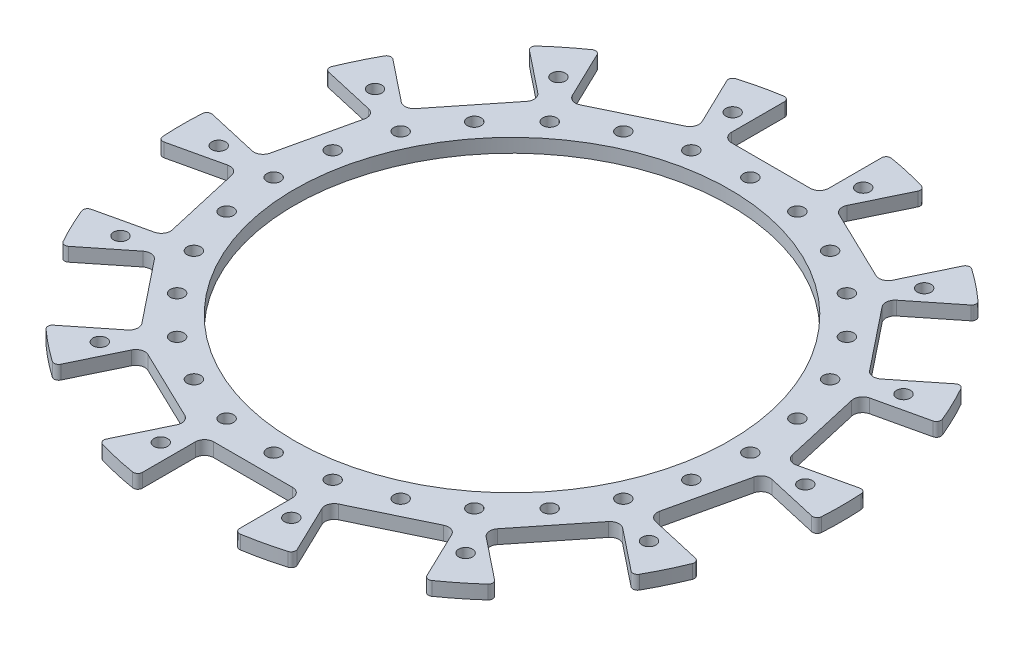
SolidWorks part; units mm, degrees
material "Thornel Mat VMA"
ref_plane "前视基准面" through (0, 0, 0) normal (0, 0, 1) x (1, 0, 0)
ref_plane "上视基准面" through (0, 0, 0) normal (0, 1, 0) x (1, 0, 0)
ref_plane "右视基准面" through (0, 0, 0) normal (1, 0, 0) x (0, 0, -1)
sketch "草图1" plane through (0, 0, 0) normal (0, 1, 0) x (1, 0, 0)
  line L0 (0, 0) -> (0, -67) construction
  line L1 (13, -67) -> (-13, -67) construction
  line L2 (-13, -68.5) -> (-13, -65.5)
  line L3 (0, -67) -> (0, -69.8) construction
  line L4 (-10.1, -69.8) -> (10.1, -69.8) construction
  line L5 (-13, -68.5) -> (-10.6, -68.5)
  line L6 (-10.6, -68.5) -> (-10.6, -71.2154)
  line L7 (-13, -65.5) -> (-10.6, -65.5)
  line L8 (-10.6, -65.5) -> (-10.6, -56.5)
  line L9 (-10.6, -56.5) -> (10.6, -56.5)
  line L10 (10.6, -68.5) -> (10.6, -71.2154)
  line L11 (13, -68.5) -> (10.6, -68.5)
  line L12 (13, -68.5) -> (13, -65.5)
  line L13 (13, -65.5) -> (10.6, -65.5)
  line L14 (10.6, -65.5) -> (10.6, -56.5)
  line L15 (-34.0647, -46.3056) -> (-14.9642, -55.5039)
  line L16 (-37.9697, -54.4143) -> (-34.0647, -46.3056)
  line L17 (-40.132, -53.373) -> (-37.9697, -54.4143)
  line L18 (-41.4336, -56.0759) -> (-40.132, -53.373)
  line L19 (-41.4336, -56.0759) -> (-39.2713, -57.1172)
  line L20 (-39.2713, -57.1172) -> (-40.4495, -59.5637)
  line L21 (-20.1708, -66.3155) -> (-21.349, -68.7621)
  line L22 (-18.0084, -67.3569) -> (-20.1708, -66.3155)
  line L23 (-18.0084, -67.3569) -> (-16.7068, -64.6539)
  line L24 (-16.7068, -64.6539) -> (-18.8691, -63.6126)
  line L25 (-18.8691, -63.6126) -> (-14.9642, -55.5039)
  line L26 (-50.7825, -26.9398) -> (-37.5645, -43.5146)
  line L27 (-57.819, -32.5512) -> (-50.7825, -26.9398)
  line L28 (-59.3153, -30.6748) -> (-57.819, -32.5512)
  line L29 (-61.6608, -32.5452) -> (-59.3153, -30.6748)
  line L30 (-61.6608, -32.5452) -> (-60.1644, -34.4216)
  line L31 (-60.1644, -34.4216) -> (-62.2875, -36.1147)
  line L32 (-46.9465, -50.9965) -> (-49.0695, -52.6895)
  line L33 (-45.4501, -52.8729) -> (-46.9465, -50.9965)
  line L34 (-45.4501, -52.8729) -> (-43.1046, -51.0024)
  line L35 (-43.1046, -51.0024) -> (-44.601, -49.126)
  line L36 (-44.601, -49.126) -> (-37.5645, -43.5146)
  line L37 (-57.4421, -2.2382) -> (-52.7247, -22.9067)
  line L38 (-66.2165, -4.2409) -> (-57.4421, -2.2382)
  line L39 (-66.7506, -1.9011) -> (-66.2165, -4.2409)
  line L40 (-69.6753, -2.5686) -> (-66.7506, -1.9011)
  line L41 (-69.6753, -2.5686) -> (-69.1413, -4.9084)
  line L42 (-69.1413, -4.9084) -> (-71.7886, -5.5127)
  line L43 (-64.4238, -25.5769) -> (-67.0712, -26.1812)
  line L44 (-63.8898, -27.9167) -> (-64.4238, -25.5769)
  line L45 (-63.8898, -27.9167) -> (-60.965, -27.2492)
  line L46 (-60.965, -27.2492) -> (-61.4991, -24.9094)
  line L47 (-61.4991, -24.9094) -> (-52.7247, -22.9067)
  line L48 (-52.7247, 22.9067) -> (-57.4421, 2.2382)
  line L49 (-61.4991, 24.9094) -> (-52.7247, 22.9067)
  line L50 (-60.965, 27.2492) -> (-61.4991, 24.9094)
  line L51 (-63.8898, 27.9167) -> (-60.965, 27.2492)
  line L52 (-63.8898, 27.9167) -> (-64.4238, 25.5769)
  line L53 (-64.4238, 25.5769) -> (-67.0712, 26.1812)
  line L54 (-69.1413, 4.9084) -> (-71.7886, 5.5127)
  line L55 (-69.6753, 2.5686) -> (-69.1413, 4.9084)
  line L56 (-69.6753, 2.5686) -> (-66.7506, 1.9011)
  line L57 (-66.7506, 1.9011) -> (-66.2165, 4.2409)
  line L58 (-66.2165, 4.2409) -> (-57.4421, 2.2382)
  line L59 (-37.5645, 43.5146) -> (-50.7825, 26.9398)
  line L60 (-44.601, 49.126) -> (-37.5645, 43.5146)
  line L61 (-43.1046, 51.0024) -> (-44.601, 49.126)
  line L62 (-45.4501, 52.8729) -> (-43.1046, 51.0024)
  line L63 (-45.4501, 52.8729) -> (-46.9465, 50.9965)
  line L64 (-46.9465, 50.9965) -> (-49.0695, 52.6895)
  line L65 (-60.1644, 34.4216) -> (-62.2875, 36.1147)
  line L66 (-61.6608, 32.5452) -> (-60.1644, 34.4216)
  line L67 (-61.6608, 32.5452) -> (-59.3153, 30.6748)
  line L68 (-59.3153, 30.6748) -> (-57.819, 32.5512)
  line L69 (-57.819, 32.5512) -> (-50.7825, 26.9398)
  line L70 (-14.9642, 55.5039) -> (-34.0647, 46.3056)
  line L71 (-18.8691, 63.6126) -> (-14.9642, 55.5039)
  line L72 (-16.7068, 64.6539) -> (-18.8691, 63.6126)
  line L73 (-18.0084, 67.3569) -> (-16.7068, 64.6539)
  line L74 (-18.0084, 67.3569) -> (-20.1708, 66.3155)
  line L75 (-20.1708, 66.3155) -> (-21.349, 68.7621)
  line L76 (-39.2713, 57.1172) -> (-40.4495, 59.5637)
  line L77 (-41.4336, 56.0759) -> (-39.2713, 57.1172)
  line L78 (-41.4336, 56.0759) -> (-40.132, 53.373)
  line L79 (-40.132, 53.373) -> (-37.9697, 54.4143)
  line L80 (-37.9697, 54.4143) -> (-34.0647, 46.3056)
  line L81 (10.6, 56.5) -> (-10.6, 56.5)
  line L82 (10.6, 65.5) -> (10.6, 56.5)
  line L83 (13, 65.5) -> (10.6, 65.5)
  line L84 (13, 68.5) -> (13, 65.5)
  line L85 (13, 68.5) -> (10.6, 68.5)
  line L86 (10.6, 68.5) -> (10.6, 71.2154)
  line L87 (-10.6, 68.5) -> (-10.6, 71.2154)
  line L88 (-13, 68.5) -> (-10.6, 68.5)
  line L89 (-13, 68.5) -> (-13, 65.5)
  line L90 (-13, 65.5) -> (-10.6, 65.5)
  line L91 (-10.6, 65.5) -> (-10.6, 56.5)
  line L92 (34.0647, 46.3056) -> (14.9642, 55.5039)
  line L93 (37.9697, 54.4143) -> (34.0647, 46.3056)
  line L94 (40.132, 53.373) -> (37.9697, 54.4143)
  line L95 (41.4336, 56.0759) -> (40.132, 53.373)
  line L96 (41.4336, 56.0759) -> (39.2713, 57.1172)
  line L97 (39.2713, 57.1172) -> (40.4495, 59.5637)
  line L98 (20.1708, 66.3155) -> (21.349, 68.7621)
  line L99 (18.0084, 67.3569) -> (20.1708, 66.3155)
  line L100 (18.0084, 67.3569) -> (16.7068, 64.6539)
  line L101 (16.7068, 64.6539) -> (18.8691, 63.6126)
  line L102 (18.8691, 63.6126) -> (14.9642, 55.5039)
  line L103 (50.7825, 26.9398) -> (37.5645, 43.5146)
  line L104 (57.819, 32.5512) -> (50.7825, 26.9398)
  line L105 (59.3153, 30.6748) -> (57.819, 32.5512)
  line L106 (61.6608, 32.5452) -> (59.3153, 30.6748)
  line L107 (61.6608, 32.5452) -> (60.1644, 34.4216)
  line L108 (60.1644, 34.4216) -> (62.2875, 36.1147)
  line L109 (46.9465, 50.9965) -> (49.0695, 52.6895)
  line L110 (45.4501, 52.8729) -> (46.9465, 50.9965)
  line L111 (45.4501, 52.8729) -> (43.1046, 51.0024)
  line L112 (43.1046, 51.0024) -> (44.601, 49.126)
  line L113 (44.601, 49.126) -> (37.5645, 43.5146)
  line L114 (57.4421, 2.2382) -> (52.7247, 22.9067)
  line L115 (66.2165, 4.2409) -> (57.4421, 2.2382)
  line L116 (66.7506, 1.9011) -> (66.2165, 4.2409)
  line L117 (69.6753, 2.5686) -> (66.7506, 1.9011)
  line L118 (69.6753, 2.5686) -> (69.1413, 4.9084)
  line L119 (69.1413, 4.9084) -> (71.7886, 5.5127)
  line L120 (64.4238, 25.5769) -> (67.0712, 26.1812)
  line L121 (63.8898, 27.9167) -> (64.4238, 25.5769)
  line L122 (63.8898, 27.9167) -> (60.965, 27.2492)
  line L123 (60.965, 27.2492) -> (61.4991, 24.9094)
  line L124 (61.4991, 24.9094) -> (52.7247, 22.9067)
  line L125 (52.7247, -22.9067) -> (57.4421, -2.2382)
  line L126 (61.4991, -24.9094) -> (52.7247, -22.9067)
  line L127 (60.965, -27.2492) -> (61.4991, -24.9094)
  line L128 (63.8898, -27.9167) -> (60.965, -27.2492)
  line L129 (63.8898, -27.9167) -> (64.4238, -25.5769)
  line L130 (64.4238, -25.5769) -> (67.0712, -26.1812)
  line L131 (69.1413, -4.9084) -> (71.7886, -5.5127)
  line L132 (69.6753, -2.5686) -> (69.1413, -4.9084)
  line L133 (69.6753, -2.5686) -> (66.7506, -1.9011)
  line L134 (66.7506, -1.9011) -> (66.2165, -4.2409)
  line L135 (66.2165, -4.2409) -> (57.4421, -2.2382)
  line L136 (37.5645, -43.5146) -> (50.7825, -26.9398)
  line L137 (44.601, -49.126) -> (37.5645, -43.5146)
  line L138 (43.1046, -51.0024) -> (44.601, -49.126)
  line L139 (45.4501, -52.8729) -> (43.1046, -51.0024)
  line L140 (45.4501, -52.8729) -> (46.9465, -50.9965)
  line L141 (46.9465, -50.9965) -> (49.0695, -52.6895)
  line L142 (60.1644, -34.4216) -> (62.2875, -36.1147)
  line L143 (61.6608, -32.5452) -> (60.1644, -34.4216)
  line L144 (61.6608, -32.5452) -> (59.3153, -30.6748)
  line L145 (59.3153, -30.6748) -> (57.819, -32.5512)
  line L146 (57.819, -32.5512) -> (50.7825, -26.9398)
  line L147 (14.9642, -55.5039) -> (34.0647, -46.3056)
  line L148 (18.8691, -63.6126) -> (14.9642, -55.5039)
  line L149 (16.7068, -64.6539) -> (18.8691, -63.6126)
  line L150 (18.0084, -67.3569) -> (16.7068, -64.6539)
  line L151 (18.0084, -67.3569) -> (20.1708, -66.3155)
  line L152 (20.1708, -66.3155) -> (21.349, -68.7621)
  line L153 (39.2713, -57.1172) -> (40.4495, -59.5637)
  line L154 (41.4336, -56.0759) -> (39.2713, -57.1172)
  line L155 (41.4336, -56.0759) -> (40.132, -53.373)
  line L156 (40.132, -53.373) -> (37.9697, -54.4143)
  line L157 (37.9697, -54.4143) -> (34.0647, -46.3056)
  line L158 (-10.6, -65.5) -> (-10.6, -68.5)
  line L159 (10.6, -65.5) -> (10.6, -68.5)
  line L160 (-18.8691, -63.6126) -> (-20.1708, -66.3155)
  line L161 (-37.9697, -54.4143) -> (-39.2713, -57.1172)
  line L162 (-44.601, -49.126) -> (-46.9465, -50.9965)
  line L163 (-57.819, -32.5512) -> (-60.1644, -34.4216)
  line L164 (-61.4991, -24.9094) -> (-64.4238, -25.5769)
  line L165 (-66.2165, -4.2409) -> (-69.1413, -4.9084)
  line L166 (-66.2165, 4.2409) -> (-69.1413, 4.9084)
  line L167 (-61.4991, 24.9094) -> (-64.4238, 25.5769)
  line L168 (-57.819, 32.5512) -> (-60.1644, 34.4216)
  line L169 (-44.601, 49.126) -> (-46.9465, 50.9965)
  line L170 (-37.9697, 54.4143) -> (-39.2713, 57.1172)
  line L171 (-18.8691, 63.6126) -> (-20.1708, 66.3155)
  line L172 (-10.6, 65.5) -> (-10.6, 68.5)
  line L173 (10.6, 65.5) -> (10.6, 68.5)
  line L174 (18.8691, 63.6126) -> (20.1708, 66.3155)
  line L175 (37.9697, 54.4143) -> (39.2713, 57.1172)
  line L176 (44.601, 49.126) -> (46.9465, 50.9965)
  line L177 (57.819, 32.5512) -> (60.1644, 34.4216)
  line L178 (61.4991, 24.9094) -> (64.4238, 25.5769)
  line L179 (66.2165, 4.2409) -> (69.1413, 4.9084)
  line L180 (66.2165, -4.2409) -> (69.1413, -4.9084)
  line L181 (61.4991, -24.9094) -> (64.4238, -25.5769)
  line L182 (57.819, -32.5512) -> (60.1644, -34.4216)
  line L183 (44.601, -49.126) -> (46.9465, -50.9965)
  line L184 (37.9697, -54.4143) -> (39.2713, -57.1172)
  line L185 (18.8691, -63.6126) -> (20.1708, -66.3155)
  circle A0 centre (0, 0) radius 67 construction
  circle A1 centre (0, 0) radius 72
  point P7 (0, -67)
  point P10 (-13, -67)
  point P18 (0, -69.8)
  point P21 (0, -69.8)
  point P26 (0, -56.5)
  point P185 (0, 0)
  point P237 (0, 0)
  dimension "D1" = 134
  dimension "D5" = 144
  dimension "D2" = 26
  dimension "D3" = 3
  dimension "D4" = 20.2
  dimension "D6" = 0.5
  dimension "D7" = 10.5
  dimension "D10" = 2.8
  dimension "D8" = 14
  dimension "D9" = 14
extrude "凸台-拉伸1" add sketch "草图1" along normal blind 3 contours L10 A1 L152 L151 L150 L149 L148 L147 L157 L156 L155 L154 L153 L141 L140 L139 L138 L137 L136 L146 L145 L144 L143 L142 L130 L129 L128 L127 L126 L125 L135 L134 L133 L132 L131 L119 L118 L117 L116 L115 L114 L124 L123 L122 L121 L120 L108 | L161 L17 L18 L19 | L163 L28 L29 L30 | L35 L162 L33 L34 | L46 L164 L44 L45 | L24 L160 L22 L23 | L158 L7 L2 L5 | L185 L149 L150 L151 | L13 L159 L11 L12 | L156 L184 L154 L155 | L183 L138 L139 L140 | L145 L182 L143 L144 | L181 L127 L128 L129 | L134 L180 L132 L133 | L179 L116 L117 L118 | L177 L105 L106 L107 | L123 L178 L121 L122 | L112 L176 L110 L111 | L175 L94 L95 L96 | L101 L174 L99 L100 | L173 L83 L84 L85 | L171 L72 L73 L74 | L90 L172 L88 L89 | L169 L61 L62 L63 | L79 L170 L77 L78 | L167 L50 L51 L52 | L68 L168 L66 L67 | L165 L39 L40 L41 | L57 L166 L55 L56
fillet "圆角1" radius 2 28 edges at (50.7825, 1.5, 26.9398) (57.4421, 1.5, 2.2382) (52.7247, 1.5, -22.9067) (37.5645, 1.5, -43.5146) (14.9642, 1.5, -55.5039) (-10.6, 1.5, -56.5) (-34.0647, 1.5, -46.3056) (-50.7825, 1.5, -26.9398) (-57.4421, 1.5, -2.2382) (-52.7247, 1.5, 22.9067) (-37.5645, 1.5, 43.5146) (-14.9642, 1.5, 55.5039) (-34.0647, 1.5, 46.3056) (-50.7825, 1.5, 26.9398) (-57.4421, 1.5, 2.2382) (-52.7247, 1.5, -22.9067) (-37.5645, 1.5, -43.5146) (-14.9642, 1.5, -55.5039) (10.6, 1.5, -56.5) (34.0647, 1.5, -46.3056) (57.4421, 1.5, -2.2382) (50.7825, 1.5, -26.9398) (52.7247, 1.5, 22.9067) (37.5645, 1.5, 43.5146) (34.0647, 1.5, 46.3056) (14.9642, 1.5, 55.5039) (10.6, 1.5, 56.5) (-10.6, 1.5, 56.5)
fillet "圆角2" radius 1 28 edges at (40.4495, 1.5, 59.5637) (10.6, 1.5, 71.2154) (62.2875, 1.5, 36.1147) (71.7886, 1.5, 5.5127) (67.0712, 1.5, -26.1812) (49.0695, 1.5, -52.6895) (21.349, 1.5, -68.7621) (-10.6, 1.5, -71.2154) (-40.4495, 1.5, -59.5637) (-62.2875, 1.5, -36.1147) (-71.7886, 1.5, -5.5127) (-67.0712, 1.5, 26.1812) (71.7886, 1.5, -5.5127) (-21.349, 1.5, 68.7621) (40.4495, 1.5, -59.5637) (-49.0695, 1.5, 52.6895) (62.2875, 1.5, -36.1147) (-40.4495, 1.5, 59.5637) (-62.2875, 1.5, 36.1147) (-71.7886, 1.5, 5.5127) (-67.0712, 1.5, -26.1812) (-49.0695, 1.5, -52.6895) (-21.349, 1.5, -68.7621) (10.6, 1.5, -71.2154) (67.0712, 1.5, 26.1812) (49.0695, 1.5, 52.6895) (21.349, 1.5, 68.7621) (-10.6, 1.5, 71.2154)
sketch "草图2" plane through (0, 0, 0) normal (0, 1, 0) x (1, 0, 0)
  line L0 (64, 0) -> (0, 0) construction
  circle A0 centre (64, 0) radius 1.5
  circle A1 centre (57.662, -27.7686) radius 1.5
  circle A2 centre (39.9033, -50.0372) radius 1.5
  circle A3 centre (14.2413, -62.3954) radius 1.5
  circle A4 centre (-14.2413, -62.3954) radius 1.5
  circle A5 centre (-39.9033, -50.0372) radius 1.5
  circle A6 centre (-57.662, -27.7686) radius 1.5
  circle A7 centre (-64, 0) radius 1.5
  circle A8 centre (-57.662, 27.7686) radius 1.5
  circle A9 centre (-39.9033, 50.0372) radius 1.5
  circle A10 centre (-14.2413, 62.3954) radius 1.5
  circle A11 centre (14.2413, 62.3954) radius 1.5
  circle A12 centre (39.9033, 50.0372) radius 1.5
  circle A13 centre (57.662, 27.7686) radius 1.5
  point P32 (0, 0)
  dimension "D1" = 3
  dimension "D2" = 64
  dimension "D3" = 14
extrude "切除-拉伸1" cut sketch "草图2" along normal blind 11
sketch "草图3" plane through (0, 0, 0) normal (0, 1, 0) x (1, 0, 0)
  line L0 (0, -56.5) -> (0, -52.5) construction
  line L1 (-8.6, -56.5) -> (8.6, -56.5) construction
  circle A0 centre (0, 0) radius 9
  circle A1 centre (0, 0) radius 28
  circle A2 centre (0, 0) radius 52.5
  dimension "D1" = 18
  dimension "D2" = 56
  dimension "D3" = 4
extrude "切除-拉伸2" cut sketch "草图3" along normal blind 11 contours A0 | A2 A1 | A1 A0
sketch "草图9" plane through (0, 3, 0) normal (0, 1, 0) x (1, 0, 0)
  circle A0 centre (0, 0) radius 52.5
  circle A1 centre (0, 0) radius 47.5
  dimension "D1" = 105
  dimension "D2" = 95
extrude "凸台-拉伸2" add sketch "草图9" against normal blind 3
sketch "草图10" plane through (0, 3, 0) normal (0, 1, 0) x (1, 0, 0)
  circle A0 centre (0, 0) radius 52 construction
  circle A1 centre (0, 52) radius 1.5
  circle A2 centre (11.5711, 50.6963) radius 1.5
  circle A3 centre (22.562, 46.8504) radius 1.5
  circle A4 centre (32.4215, 40.6552) radius 1.5
  circle A5 centre (40.6552, 32.4215) radius 1.5
  circle A6 centre (46.8504, 22.562) radius 1.5
  circle A7 centre (50.6963, 11.5711) radius 1.5
  circle A8 centre (52, 0) radius 1.5
  circle A9 centre (50.6963, -11.5711) radius 1.5
  circle A10 centre (46.8504, -22.562) radius 1.5
  circle A11 centre (40.6552, -32.4215) radius 1.5
  circle A12 centre (32.4215, -40.6552) radius 1.5
  circle A13 centre (22.562, -46.8504) radius 1.5
  circle A14 centre (11.5711, -50.6963) radius 1.5
  circle A15 centre (0, -52) radius 1.5
  circle A16 centre (-11.5711, -50.6963) radius 1.5
  circle A17 centre (-22.562, -46.8504) radius 1.5
  circle A18 centre (-32.4215, -40.6552) radius 1.5
  circle A19 centre (-40.6552, -32.4215) radius 1.5
  circle A20 centre (-46.8504, -22.562) radius 1.5
  circle A21 centre (-50.6963, -11.5711) radius 1.5
  circle A22 centre (-52, 0) radius 1.5
  circle A23 centre (-50.6963, 11.5711) radius 1.5
  circle A24 centre (-46.8504, 22.562) radius 1.5
  circle A25 centre (-40.6552, 32.4215) radius 1.5
  circle A26 centre (-32.4215, 40.6552) radius 1.5
  circle A27 centre (-22.562, 46.8504) radius 1.5
  circle A28 centre (-11.5711, 50.6963) radius 1.5
  point P62 (0, 0)
  dimension "D1" = 104
  dimension "D2" = 3
  dimension "D3" = 28
extrude "切除-拉伸3" cut sketch "草图10" against normal blind 3
